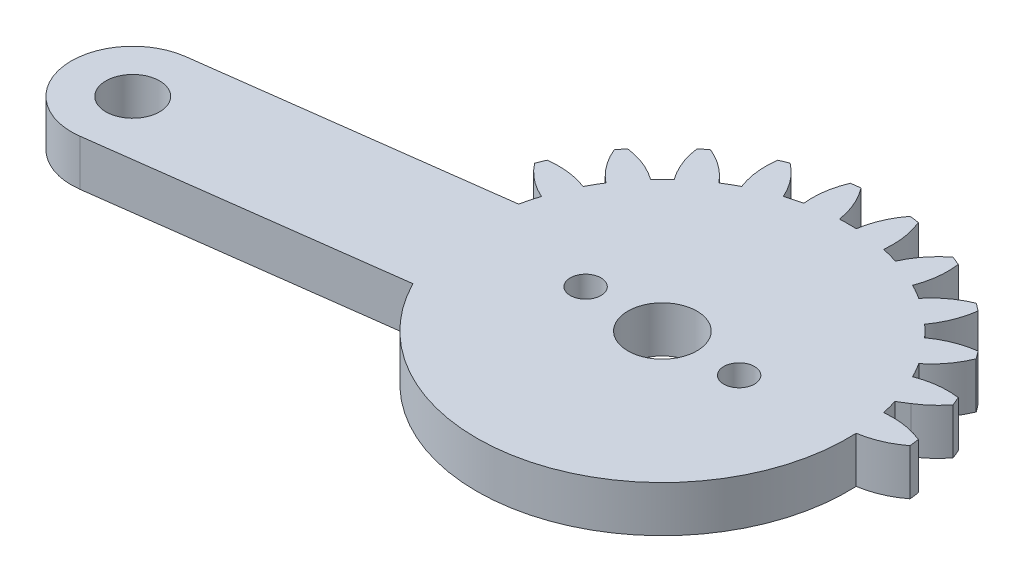
SolidWorks part; units mm, degrees
ref_plane "Front Plane" through (0, 0, 0) normal (0, 0, 1) x (1, 0, 0)
ref_plane "Top Plane" through (0, 0, 0) normal (0, 1, 0) x (1, 0, 0)
ref_plane "Right Plane" through (0, 0, 0) normal (1, 0, 0) x (0, 0, -1)
sketch "Sketch1" plane through (0, 0, 0) normal (0, 1, 0) x (1, 0, 0)
  line L0 (20.6437, 4) -> (2.0816, 4)
  line L1 (2.0816, -4) -> (20.6437, -4)
  arc A0 (2.0816, 4) -> (3.5217, 5.3071) centre (-0.7683, 8.5867) ccw
  arc A1 (3.5217, 5.3071) -> (3.2829, 5.8838) centre (-10.1063, 0) ccw
  arc A2 (3.2829, 5.8838) -> (0.6271, 5.5703) centre (2.5684, 0.5313) ccw
  arc A3 (0.6271, 5.5703) -> (0.0844, 6.5103) centre (-10.1063, 0) ccw
  arc A4 (0.0844, 6.5103) -> (1.6838, 8.6535) centre (-3.3089, 10.711) ccw
  arc A5 (1.6838, 8.6535) -> (1.3038, 9.1487) centre (-10.1063, 0) ccw
  arc A6 (1.3038, 9.1487) -> (-1.1803, 8.1585) centre (1.999, 3.7936) ccw
  arc A7 (-1.1803, 8.1585) -> (-1.9479, 8.926) centre (-10.1063, 0) ccw
  arc A8 (-1.9479, 8.926) -> (-0.9576, 11.4102) centre (-6.3127, 12.1053) ccw
  arc A9 (-0.9576, 11.4102) -> (-1.4528, 11.7901) centre (-10.1063, 0) ccw
  arc A10 (-1.4528, 11.7901) -> (-3.596, 10.1907) centre (0.6046, 6.7975) ccw
  arc A11 (-3.596, 10.1907) -> (-4.5361, 10.7334) centre (-10.1063, 0) ccw
  arc A12 (-4.5361, 10.7334) -> (-4.2225, 13.3892) centre (-9.5751, 12.6747) ccw
  arc A13 (-4.2225, 13.3892) -> (-4.7992, 13.6281) centre (-10.1063, 0) ccw
  arc A14 (-4.7992, 13.6281) -> (-6.4554, 11.5285) centre (-1.5196, 9.3381) ccw
  arc A15 (-6.4554, 11.5285) -> (-7.5039, 11.8094) centre (-10.1063, 0) ccw
  arc A16 (-7.5039, 11.8094) -> (-7.8884, 14.4558) centre (-12.8736, 12.3803) ccw
  arc A17 (-7.8884, 14.4558) -> (-8.5072, 14.5373) centre (-10.1063, 0) ccw
  arc A18 (-8.5072, 14.5373) -> (-9.5636, 12.0806) centre (-4.2291, 11.2423) ccw
  arc A19 (-9.5636, 12.0806) -> (-10.6491, 12.0806) centre (-10.1063, 0) ccw
  arc A20 (-10.6491, 12.0806) -> (-11.7054, 14.5373) centre (-15.9836, 11.2423) ccw
  arc A21 (-11.7054, 14.5373) -> (-12.3243, 14.4558) centre (-10.1063, 0) ccw
  arc A22 (-12.3243, 14.4558) -> (-12.7088, 11.8094) centre (-7.3391, 12.3803) ccw
  arc A23 (-12.7088, 11.8094) -> (-13.7573, 11.5285) centre (-10.1063, 0) ccw
  arc A24 (-13.7573, 11.5285) -> (-15.4135, 13.6281) centre (-18.6931, 9.3381) ccw
  arc A25 (-15.4135, 13.6281) -> (-15.9901, 13.3892) centre (-10.1063, 0) ccw
  arc A26 (-15.9901, 13.3892) -> (-15.6766, 10.7334) centre (-10.6376, 12.6747) ccw
  arc A27 (-15.6766, 10.7334) -> (-16.6166, 10.1907) centre (-10.1063, 0) ccw
  arc A28 (-16.6166, 10.1907) -> (-18.7599, 11.7901) centre (-20.8173, 6.7975) ccw
  arc A29 (-18.7599, 11.7901) -> (-19.255, 11.4102) centre (-10.1063, 0) ccw
  arc A30 (-19.255, 11.4102) -> (-18.2648, 8.926) centre (-13.9, 12.1053) ccw
  arc A31 (-18.2648, 8.926) -> (-19.0324, 8.1585) centre (-10.1063, 0) ccw
  arc A32 (-19.0324, 8.1585) -> (-21.5165, 9.1487) centre (-22.2117, 3.7936) ccw
  arc A33 (-21.5165, 9.1487) -> (-21.8965, 8.6535) centre (-10.1063, 0) ccw
  arc A34 (-21.8965, 8.6535) -> (-20.2971, 6.5103) centre (-16.9038, 10.711) ccw
  arc A35 (-20.2971, 6.5103) -> (-20.8398, 5.5703) centre (-10.1063, 0) ccw
  arc A36 (-20.8398, 5.5703) -> (-23.4956, 5.8838) centre (-22.7811, 0.5313) ccw
  arc A37 (-23.4956, 5.8838) -> (-23.7344, 5.3071) centre (-10.1063, 0) ccw
  arc A38 (-23.7344, 5.3071) -> (-21.6348, 3.6509) centre (-19.4444, 8.5867) ccw
  arc A39 (-21.6348, 3.6509) -> (-21.9157, 2.6025) centre (-10.1063, 0) ccw
  arc A40 (-21.9157, 2.6025) -> (-24.5622, 2.2179) centre (-22.4867, -2.7673) ccw
  arc A41 (-24.5622, 2.2179) -> (-24.6437, 1.5991) centre (-10.1063, 0) ccw
  arc A42 (-24.6437, 1.5991) -> (-22.1869, 0.5427) centre (-21.3486, 5.8773) ccw
  arc A43 (-22.1869, 0.5427) -> (-22.1869, -0.5427) centre (-10.1063, 0) ccw
  arc A44 (-22.1869, -0.5427) -> (-24.6437, -1.5991) centre (-21.3486, -5.8773) ccw
  arc A45 (-24.6437, -1.5991) -> (-24.5622, -2.2179) centre (-10.1063, 0) ccw
  arc A46 (-24.5622, -2.2179) -> (-21.9157, -2.6025) centre (-22.4867, 2.7673) ccw
  arc A47 (-21.9157, -2.6025) -> (-21.6348, -3.6509) centre (-10.1063, 0) ccw
  arc A48 (-21.6348, -3.6509) -> (-23.7344, -5.3071) centre (-19.4444, -8.5867) ccw
  arc A49 (-23.7344, -5.3071) -> (-23.4956, -5.8838) centre (-10.1063, 0) ccw
  arc A50 (-23.4956, -5.8838) -> (-20.8398, -5.5703) centre (-22.7811, -0.5313) ccw
  arc A51 (-20.8398, -5.5703) -> (-20.2971, -6.5103) centre (-10.1063, 0) ccw
  arc A52 (-20.2971, -6.5103) -> (-21.8965, -8.6535) centre (-16.9038, -10.711) ccw
  arc A53 (-21.8965, -8.6535) -> (-21.5165, -9.1487) centre (-10.1063, 0) ccw
  arc A54 (-21.5165, -9.1487) -> (-19.0324, -8.1585) centre (-22.2117, -3.7936) ccw
  arc A55 (-19.0324, -8.1585) -> (-18.2648, -8.926) centre (-10.1063, 0) ccw
  arc A56 (-18.2648, -8.926) -> (-19.255, -11.4102) centre (-13.9, -12.1053) ccw
  arc A57 (-19.255, -11.4102) -> (-18.7599, -11.7901) centre (-10.1063, 0) ccw
  arc A58 (-18.7599, -11.7901) -> (-16.6166, -10.1907) centre (-20.8173, -6.7975) ccw
  arc A59 (-16.6166, -10.1907) -> (-15.6766, -10.7334) centre (-10.1063, 0) ccw
  arc A60 (-15.6766, -10.7334) -> (-15.9901, -13.3892) centre (-10.6376, -12.6747) ccw
  arc A61 (-15.9901, -13.3892) -> (-15.4135, -13.6281) centre (-10.1063, 0) ccw
  arc A62 (-15.4135, -13.6281) -> (-13.7573, -11.5285) centre (-18.6931, -9.3381) ccw
  arc A63 (-13.7573, -11.5285) -> (-12.7088, -11.8094) centre (-10.1063, 0) ccw
  arc A64 (-12.7088, -11.8094) -> (-12.3243, -14.4558) centre (-7.3391, -12.3803) ccw
  arc A65 (-12.3243, -14.4558) -> (-11.7054, -14.5373) centre (-10.1063, 0) ccw
  arc A66 (-11.7054, -14.5373) -> (-10.6491, -12.0806) centre (-15.9836, -11.2423) ccw
  arc A67 (-10.6491, -12.0806) -> (-9.5636, -12.0806) centre (-10.1063, 0) ccw
  arc A68 (-9.5636, -12.0806) -> (-8.5072, -14.5373) centre (-4.2291, -11.2423) ccw
  arc A69 (-8.5072, -14.5373) -> (-7.8884, -14.4558) centre (-10.1063, 0) ccw
  arc A70 (-7.8884, -14.4558) -> (-7.5039, -11.8094) centre (-12.8736, -12.3803) ccw
  arc A71 (-7.5039, -11.8094) -> (-6.4554, -11.5285) centre (-10.1063, 0) ccw
  arc A72 (-6.4554, -11.5285) -> (-4.7992, -13.6281) centre (-1.5196, -9.3381) ccw
  arc A73 (-4.7992, -13.6281) -> (-4.2225, -13.3892) centre (-10.1063, 0) ccw
  arc A74 (-4.2225, -13.3892) -> (-4.5361, -10.7334) centre (-9.5751, -12.6747) ccw
  arc A75 (-4.5361, -10.7334) -> (-3.596, -10.1907) centre (-10.1063, 0) ccw
  arc A76 (-3.596, -10.1907) -> (-1.4528, -11.7901) centre (0.6046, -6.7975) ccw
  arc A77 (-1.4528, -11.7901) -> (-0.9576, -11.4102) centre (-10.1063, 0) ccw
  arc A78 (-0.9576, -11.4102) -> (-1.9479, -8.926) centre (-6.3127, -12.1053) ccw
  arc A79 (-1.9479, -8.926) -> (-1.1803, -8.1585) centre (-10.1063, 0) ccw
  arc A80 (-1.1803, -8.1585) -> (1.3038, -9.1487) centre (1.999, -3.7936) ccw
  arc A81 (1.3038, -9.1487) -> (1.6838, -8.6535) centre (-10.1063, 0) ccw
  arc A82 (1.6838, -8.6535) -> (0.0844, -6.5103) centre (-3.3089, -10.711) ccw
  arc A83 (0.0844, -6.5103) -> (0.6271, -5.5703) centre (-10.1063, 0) ccw
  arc A84 (0.6271, -5.5703) -> (3.2829, -5.8838) centre (2.5684, -0.5313) ccw
  arc A85 (3.2829, -5.8838) -> (3.5217, -5.3071) centre (-10.1063, 0) ccw
  arc A86 (3.5217, -5.3071) -> (2.0816, -4) centre (-0.7683, -8.5867) ccw
  arc A87 (20.6437, -4) -> (20.6437, 4) centre (20.6437, 0) ccw
  circle A88 centre (-10.1063, 0) radius 1.5
  circle A89 centre (20.6437, 0) radius 1.5
  dimension "D1" = 3
  dimension "D2" = 3
extrude "Boss-Extrude1" add sketch "Sketch1" along normal blind 3
sketch "Sketch3" plane through (0, 3, 0) normal (0, 1, 0) x (1, 0, 0)
  line L0 (-10.1063, 0) -> (-40.8563, 0) construction
  line L1 (-10.1063, 0) -> (-40.5933, -4.0137)
  line L2 (-10.6284, 3.9658) -> (-41.1154, -0.0479)
  line L3 (-9.5842, -3.9658) -> (-40.0712, -7.9795)
  line L4 (-10.1063, 0) -> (-4.5096, 13.5117) construction
  line L5 (-10.1063, 0) -> (-8.1974, 14.4999) construction
  circle A0 centre (-10.1063, 0) radius 1.5
  circle A1 centre (20.6437, 0) radius 1.5 construction
  circle A2 centre (20.6437, 0) radius 1.5
  circle A3 centre (-40.5933, -4.0137) radius 1.75
  circle A4 centre (-40.5933, -4.0137) radius 4
  circle A5 centre (-10.1063, 0) radius 4
  arc A6 (-4.2225, 13.3892) -> (-4.7992, 13.6281) centre (-10.1063, 0) ccw construction
  arc A7 (-7.8884, 14.4558) -> (-8.5072, 14.5373) centre (-10.1063, 0) ccw construction
  dimension "D2" = 3
  dimension "D5" = 3.5
  dimension "D6" = 8
  dimension "D7" = 8
  dimension "D1" = 30.75
  dimension "D4" = 7.5
extrude "Boss-Extrude2" add sketch "Sketch3" against normal blind 3
sketch "Sketch4" plane through (0, 3, 0) normal (0, 1, 0) x (1, 0, 0)
  line L0 (20.6437, 4) -> (2.0816, 4) construction
  line L1 (2.0816, -4) -> (20.6437, -4) construction
  line L2 (20.6437, 4) -> (2.0816, 4)
  line L3 (2.0816, -4) -> (20.6437, -4)
  line L4 (2.0816, 4) -> (1.4381, 3.6001)
  line L5 (-21.6245, -5.5509) -> (-20.8986, -5.4553)
  line L6 (-10.1063, 0) -> (0.0844, 6.5103) construction
  line L7 (-10.1063, 0) -> (1.9742, 0.5427) construction
  line L8 (-24.5755, 2.1296) -> (-41.1154, -0.0479)
  line L9 (-40.0712, -7.9795) -> (-23.5312, -5.8019)
  line L10 (2.0816, -4) -> (20.6437, -4)
  line L11 (2.0816, -4) -> (20.6437, -4)
  line L12 (-21.9429, 2.4762) -> (-41.1154, -0.0479)
  line L13 (-40.0712, -7.9795) -> (-21.6245, -5.5509)
  line L18 (20.6437, 4) -> (2.0816, 4)
  line L19 (20.6437, 4) -> (2.0816, 4)
  circle A0 centre (-10.1063, 0) radius 12.0927
  arc A1 (3.2829, 5.8838) -> (0.6271, 5.5703) centre (2.5684, 0.5313) ccw construction
  arc A2 (3.5217, 5.3071) -> (3.2829, 5.8838) centre (-10.1063, 0) ccw construction
  arc A3 (2.0816, 4) -> (3.5217, 5.3071) centre (-0.7683, 8.5867) ccw construction
  arc A4 (20.6437, -4) -> (20.6437, 4) centre (20.6437, 0) ccw construction
  arc A5 (3.5217, -5.3071) -> (2.0816, -4) centre (-0.7683, -8.5867) ccw construction
  arc A6 (3.2829, -5.8838) -> (3.5217, -5.3071) centre (-10.1063, 0) ccw construction
  arc A7 (0.6271, -5.5703) -> (3.2829, -5.8838) centre (2.5684, -0.5313) ccw construction
  arc A8 (3.2829, 5.8838) -> (0.6271, 5.5703) centre (2.5684, 0.5313) ccw
  arc A9 (3.5217, 5.3071) -> (3.2829, 5.8838) centre (-10.1063, 0) ccw
  arc A10 (2.0816, 4) -> (3.5217, 5.3071) centre (-0.7683, 8.5867) ccw
  arc A11 (20.6437, -4) -> (20.6437, 4) centre (20.6437, 0) ccw
  arc A12 (3.5217, -5.3071) -> (2.0816, -4) centre (-0.7683, -8.5867) ccw
  arc A13 (3.2829, -5.8838) -> (3.5217, -5.3071) centre (-10.1063, 0) ccw
  arc A14 (0.6271, -5.5703) -> (3.2829, -5.8838) centre (2.5684, -0.5313) ccw
  arc A15 (1.9742, 0.5427) -> (4.431, 1.5991) centre (1.1359, 5.8773) ccw
  arc A16 (4.3495, 2.2179) -> (1.7031, 2.6025) centre (2.274, -2.7673) ccw
  arc A17 (4.431, 1.5991) -> (4.3495, 2.2179) centre (-10.1063, 0) ccw
  arc A64 (-20.2971, -6.5103) -> (-21.8965, -8.6535) centre (-16.9038, -10.711) ccw
  arc A65 (-20.2971, -6.5103) -> (-21.8965, -8.6535) centre (-16.9038, -10.711) ccw
  arc A66 (-21.8965, -8.6535) -> (-21.5165, -9.1487) centre (-10.1063, 0) ccw
  arc A67 (-21.8965, -8.6535) -> (-21.5165, -9.1487) centre (-10.1063, 0) ccw
  arc A68 (-21.5165, -9.1487) -> (-19.0324, -8.1585) centre (-22.2117, -3.7936) ccw
  arc A69 (-21.5165, -9.1487) -> (-19.0324, -8.1585) centre (-22.2117, -3.7936) ccw
  arc A70 (-18.2648, -8.926) -> (-19.255, -11.4102) centre (-13.9, -12.1053) ccw
  arc A71 (-18.2648, -8.926) -> (-19.255, -11.4102) centre (-13.9, -12.1053) ccw
  arc A95 (-21.6348, 3.6509) -> (-21.9157, 2.6025) centre (-10.1063, 0) ccw
  arc A96 (-41.1154, -0.0479) -> (-40.0712, -7.9795) centre (-40.5933, -4.0137) ccw
  arc A100 (-19.0324, -8.1585) -> (-18.2648, -8.926) centre (-10.1063, 0) ccw
  arc A111 (-19.255, -11.4102) -> (-18.7599, -11.7901) centre (-10.1063, 0) ccw
  arc A112 (-19.255, -11.4102) -> (-18.7599, -11.7901) centre (-10.1063, 0) ccw
  arc A113 (-18.7599, -11.7901) -> (-16.6166, -10.1907) centre (-20.8173, -6.7975) ccw
  arc A114 (-18.7599, -11.7901) -> (-16.6166, -10.1907) centre (-20.8173, -6.7975) ccw
  arc A115 (-16.6166, -10.1907) -> (-15.6766, -10.7334) centre (-10.1063, 0) ccw
  arc A116 (-16.6166, -10.1907) -> (-15.6766, -10.7334) centre (-10.1063, 0) ccw
  arc A117 (-15.6766, -10.7334) -> (-15.9901, -13.3892) centre (-10.6376, -12.6747) ccw
  arc A118 (-15.6766, -10.7334) -> (-15.9901, -13.3892) centre (-10.6376, -12.6747) ccw
  arc A119 (-15.9901, -13.3892) -> (-15.4135, -13.6281) centre (-10.1063, 0) ccw
  arc A120 (-15.9901, -13.3892) -> (-15.4135, -13.6281) centre (-10.1063, 0) ccw
  arc A121 (-15.4135, -13.6281) -> (-13.7573, -11.5285) centre (-18.6931, -9.3381) ccw
  arc A122 (-15.4135, -13.6281) -> (-13.7573, -11.5285) centre (-18.6931, -9.3381) ccw
  arc A123 (-13.7573, -11.5285) -> (-12.7088, -11.8094) centre (-10.1063, 0) ccw
  arc A124 (-13.7573, -11.5285) -> (-12.7088, -11.8094) centre (-10.1063, 0) ccw
  arc A125 (-12.7088, -11.8094) -> (-12.3243, -14.4558) centre (-7.3391, -12.3803) ccw
  arc A126 (-12.7088, -11.8094) -> (-12.3243, -14.4558) centre (-7.3391, -12.3803) ccw
  arc A127 (-12.3243, -14.4558) -> (-11.7054, -14.5373) centre (-10.1063, 0) ccw
  arc A128 (-12.3243, -14.4558) -> (-11.7054, -14.5373) centre (-10.1063, 0) ccw
  arc A129 (-11.7054, -14.5373) -> (-10.6491, -12.0806) centre (-15.9836, -11.2423) ccw
  arc A130 (-11.7054, -14.5373) -> (-10.6491, -12.0806) centre (-15.9836, -11.2423) ccw
  arc A131 (-10.6491, -12.0806) -> (-9.5636, -12.0806) centre (-10.1063, 0) ccw
  arc A132 (-10.6491, -12.0806) -> (-9.5636, -12.0806) centre (-10.1063, 0) ccw
  arc A133 (2.0816, 4) -> (3.5217, 5.3071) centre (-0.7683, 8.5867) ccw
  arc A134 (3.5217, 5.3071) -> (3.2829, 5.8838) centre (-10.1063, 0) ccw
  arc A135 (3.2829, 5.8838) -> (0.6271, 5.5703) centre (2.5684, 0.5313) ccw
  arc A136 (0.6271, 5.5703) -> (0.0844, 6.5103) centre (-10.1063, 0) ccw
  arc A137 (0.0844, 6.5103) -> (1.6838, 8.6535) centre (-3.3089, 10.711) ccw
  arc A138 (1.6838, 8.6535) -> (1.3038, 9.1487) centre (-10.1063, 0) ccw
  arc A139 (1.3038, 9.1487) -> (-1.1803, 8.1585) centre (1.999, 3.7936) ccw
  arc A140 (-1.1803, 8.1585) -> (-1.9479, 8.926) centre (-10.1063, 0) ccw
  arc A141 (-1.9479, 8.926) -> (-0.9576, 11.4102) centre (-6.3127, 12.1053) ccw
  arc A142 (-0.9576, 11.4102) -> (-1.4528, 11.7901) centre (-10.1063, 0) ccw
  arc A143 (-1.4528, 11.7901) -> (-3.596, 10.1907) centre (0.6046, 6.7975) ccw
  arc A144 (-3.596, 10.1907) -> (-4.5361, 10.7334) centre (-10.1063, 0) ccw
  arc A145 (-4.5361, 10.7334) -> (-4.2225, 13.3892) centre (-9.5751, 12.6747) ccw
  arc A146 (-4.2225, 13.3892) -> (-4.7992, 13.6281) centre (-10.1063, 0) ccw
  arc A147 (-4.7992, 13.6281) -> (-6.4554, 11.5285) centre (-1.5196, 9.3381) ccw
  arc A148 (-6.4554, 11.5285) -> (-7.5039, 11.8094) centre (-10.1063, 0) ccw
  arc A149 (-7.5039, 11.8094) -> (-7.8884, 14.4558) centre (-12.8736, 12.3803) ccw
  arc A150 (-7.8884, 14.4558) -> (-8.5072, 14.5373) centre (-10.1063, 0) ccw
  arc A151 (-8.5072, 14.5373) -> (-9.5636, 12.0806) centre (-4.2291, 11.2423) ccw
  arc A152 (-9.5636, 12.0806) -> (-10.6491, 12.0806) centre (-10.1063, 0) ccw
  arc A153 (-10.6491, 12.0806) -> (-11.7054, 14.5373) centre (-15.9836, 11.2423) ccw
  arc A154 (-11.7054, 14.5373) -> (-12.3243, 14.4558) centre (-10.1063, 0) ccw
  arc A155 (-12.3243, 14.4558) -> (-12.7088, 11.8094) centre (-7.3391, 12.3803) ccw
  arc A156 (-12.7088, 11.8094) -> (-13.7573, 11.5285) centre (-10.1063, 0) ccw
  arc A157 (-13.7573, 11.5285) -> (-15.4135, 13.6281) centre (-18.6931, 9.3381) ccw
  arc A158 (-15.4135, 13.6281) -> (-15.9901, 13.3892) centre (-10.1063, 0) ccw
  arc A159 (-15.9901, 13.3892) -> (-15.6766, 10.7334) centre (-10.6376, 12.6747) ccw
  arc A160 (-15.6766, 10.7334) -> (-16.6166, 10.1907) centre (-10.1063, 0) ccw
  arc A161 (-16.6166, 10.1907) -> (-18.7599, 11.7901) centre (-20.8173, 6.7975) ccw
  arc A162 (-18.7599, 11.7901) -> (-19.255, 11.4102) centre (-10.1063, 0) ccw
  arc A163 (-19.255, 11.4102) -> (-18.2648, 8.926) centre (-13.9, 12.1053) ccw
  arc A164 (-18.2648, 8.926) -> (-19.0324, 8.1585) centre (-10.1063, 0) ccw
  arc A165 (-19.0324, 8.1585) -> (-21.5165, 9.1487) centre (-22.2117, 3.7936) ccw
  arc A166 (-21.5165, 9.1487) -> (-21.8965, 8.6535) centre (-10.1063, 0) ccw
  arc A167 (-21.8965, 8.6535) -> (-20.2971, 6.5103) centre (-16.9038, 10.711) ccw
  arc A168 (-20.2971, 6.5103) -> (-20.8398, 5.5703) centre (-10.1063, 0) ccw
  arc A169 (-20.8398, 5.5703) -> (-23.4956, 5.8838) centre (-22.7811, 0.5313) ccw
  arc A170 (-23.4956, 5.8838) -> (-23.7344, 5.3071) centre (-10.1063, 0) ccw
  arc A171 (-23.7344, 5.3071) -> (-21.6348, 3.6509) centre (-19.4444, 8.5867) ccw
  arc A172 (-21.6348, 3.6509) -> (-21.9157, 2.6025) centre (-10.1063, 0) ccw
  arc A173 (-9.5636, -12.0806) -> (-8.5072, -14.5373) centre (-4.2291, -11.2423) ccw
  arc A174 (-9.5636, -12.0806) -> (-8.5072, -14.5373) centre (-4.2291, -11.2423) ccw
  arc A175 (-8.5072, -14.5373) -> (-7.8884, -14.4558) centre (-10.1063, 0) ccw
  arc A176 (-41.1154, -0.0479) -> (-40.0712, -7.9795) centre (-40.5933, -4.0137) ccw
  arc A177 (-8.5072, -14.5373) -> (-7.8884, -14.4558) centre (-10.1063, 0) ccw
  arc A178 (-7.8884, -14.4558) -> (-7.5039, -11.8094) centre (-12.8736, -12.3803) ccw
  arc A179 (-7.8884, -14.4558) -> (-7.5039, -11.8094) centre (-12.8736, -12.3803) ccw
  arc A180 (-19.0324, -8.1585) -> (-18.2648, -8.926) centre (-10.1063, 0) ccw
  arc A181 (-7.5039, -11.8094) -> (-6.4554, -11.5285) centre (-10.1063, 0) ccw
  arc A182 (-7.5039, -11.8094) -> (-6.4554, -11.5285) centre (-10.1063, 0) ccw
  arc A183 (-6.4554, -11.5285) -> (-4.7992, -13.6281) centre (-1.5196, -9.3381) ccw
  arc A184 (-6.4554, -11.5285) -> (-4.7992, -13.6281) centre (-1.5196, -9.3381) ccw
  arc A185 (-4.7992, -13.6281) -> (-4.2225, -13.3892) centre (-10.1063, 0) ccw
  arc A186 (-4.7992, -13.6281) -> (-4.2225, -13.3892) centre (-10.1063, 0) ccw
  arc A187 (-4.2225, -13.3892) -> (-4.5361, -10.7334) centre (-9.5751, -12.6747) ccw
  arc A188 (-4.2225, -13.3892) -> (-4.5361, -10.7334) centre (-9.5751, -12.6747) ccw
  arc A189 (-4.5361, -10.7334) -> (-3.596, -10.1907) centre (-10.1063, 0) ccw
  arc A190 (-4.5361, -10.7334) -> (-3.596, -10.1907) centre (-10.1063, 0) ccw
  arc A191 (-3.596, -10.1907) -> (-1.4528, -11.7901) centre (0.6046, -6.7975) ccw
  arc A192 (-3.596, -10.1907) -> (-1.4528, -11.7901) centre (0.6046, -6.7975) ccw
  arc A193 (-1.4528, -11.7901) -> (-0.9576, -11.4102) centre (-10.1063, 0) ccw
  arc A194 (-1.4528, -11.7901) -> (-0.9576, -11.4102) centre (-10.1063, 0) ccw
  arc A195 (-0.9576, -11.4102) -> (-1.9479, -8.926) centre (-6.3127, -12.1053) ccw
  arc A196 (-0.9576, -11.4102) -> (-1.9479, -8.926) centre (-6.3127, -12.1053) ccw
  arc A197 (-1.9479, -8.926) -> (-1.1803, -8.1585) centre (-10.1063, 0) ccw
  arc A198 (-1.9479, -8.926) -> (-1.1803, -8.1585) centre (-10.1063, 0) ccw
  arc A199 (-1.1803, -8.1585) -> (1.3038, -9.1487) centre (1.999, -3.7936) ccw
  arc A200 (-1.1803, -8.1585) -> (1.3038, -9.1487) centre (1.999, -3.7936) ccw
  arc A201 (1.3038, -9.1487) -> (1.6838, -8.6535) centre (-10.1063, 0) ccw
  arc A202 (1.3038, -9.1487) -> (1.6838, -8.6535) centre (-10.1063, 0) ccw
  arc A203 (1.6838, -8.6535) -> (0.0844, -6.5103) centre (-3.3089, -10.711) ccw
  arc A204 (1.6838, -8.6535) -> (0.0844, -6.5103) centre (-3.3089, -10.711) ccw
  arc A205 (0.0844, -6.5103) -> (0.6271, -5.5703) centre (-10.1063, 0) ccw
  arc A206 (0.0844, -6.5103) -> (0.6271, -5.5703) centre (-10.1063, 0) ccw
  arc A207 (0.6271, -5.5703) -> (3.2829, -5.8838) centre (2.5684, -0.5313) ccw
  arc A208 (0.6271, -5.5703) -> (3.2829, -5.8838) centre (2.5684, -0.5313) ccw
  arc A209 (3.2829, -5.8838) -> (3.5217, -5.3071) centre (-10.1063, 0) ccw
  arc A210 (3.2829, -5.8838) -> (3.5217, -5.3071) centre (-10.1063, 0) ccw
  arc A211 (3.5217, -5.3071) -> (2.0816, -4) centre (-0.7683, -8.5867) ccw
  arc A212 (3.5217, -5.3071) -> (2.0816, -4) centre (-0.7683, -8.5867) ccw
  arc A213 (2.0816, 4) -> (3.5217, 5.3071) centre (-0.7683, 8.5867) ccw
  arc A214 (3.5217, 5.3071) -> (3.2829, 5.8838) centre (-10.1063, 0) ccw
  arc A215 (3.2829, 5.8838) -> (0.6271, 5.5703) centre (2.5684, 0.5313) ccw
  arc A216 (0.6271, 5.5703) -> (0.0844, 6.5103) centre (-10.1063, 0) ccw
  arc A217 (0.0844, 6.5103) -> (1.6838, 8.6535) centre (-3.3089, 10.711) ccw
  arc A218 (1.6838, 8.6535) -> (1.3038, 9.1487) centre (-10.1063, 0) ccw
  arc A219 (1.3038, 9.1487) -> (-1.1803, 8.1585) centre (1.999, 3.7936) ccw
  arc A220 (-1.1803, 8.1585) -> (-1.9479, 8.926) centre (-10.1063, 0) ccw
  arc A221 (-1.9479, 8.926) -> (-0.9576, 11.4102) centre (-6.3127, 12.1053) ccw
  arc A222 (-0.9576, 11.4102) -> (-1.4528, 11.7901) centre (-10.1063, 0) ccw
  arc A223 (-1.4528, 11.7901) -> (-3.596, 10.1907) centre (0.6046, 6.7975) ccw
  arc A224 (-3.596, 10.1907) -> (-4.5361, 10.7334) centre (-10.1063, 0) ccw
  arc A225 (-4.5361, 10.7334) -> (-4.2225, 13.3892) centre (-9.5751, 12.6747) ccw
  arc A226 (-4.2225, 13.3892) -> (-4.7992, 13.6281) centre (-10.1063, 0) ccw
  arc A227 (-4.7992, 13.6281) -> (-6.4554, 11.5285) centre (-1.5196, 9.3381) ccw
  arc A228 (-6.4554, 11.5285) -> (-7.5039, 11.8094) centre (-10.1063, 0) ccw
  arc A229 (-7.5039, 11.8094) -> (-7.8884, 14.4558) centre (-12.8736, 12.3803) ccw
  arc A230 (-7.8884, 14.4558) -> (-8.5072, 14.5373) centre (-10.1063, 0) ccw
  arc A231 (-8.5072, 14.5373) -> (-9.5636, 12.0806) centre (-4.2291, 11.2423) ccw
  arc A232 (-9.5636, 12.0806) -> (-10.6491, 12.0806) centre (-10.1063, 0) ccw
  arc A233 (-10.6491, 12.0806) -> (-11.7054, 14.5373) centre (-15.9836, 11.2423) ccw
  arc A234 (-11.7054, 14.5373) -> (-12.3243, 14.4558) centre (-10.1063, 0) ccw
  arc A235 (-12.3243, 14.4558) -> (-12.7088, 11.8094) centre (-7.3391, 12.3803) ccw
  arc A236 (-12.7088, 11.8094) -> (-13.7573, 11.5285) centre (-10.1063, 0) ccw
  arc A237 (-13.7573, 11.5285) -> (-15.4135, 13.6281) centre (-18.6931, 9.3381) ccw
  arc A238 (-15.4135, 13.6281) -> (-15.9901, 13.3892) centre (-10.1063, 0) ccw
  arc A239 (-15.9901, 13.3892) -> (-15.6766, 10.7334) centre (-10.6376, 12.6747) ccw
  arc A240 (-15.6766, 10.7334) -> (-16.6166, 10.1907) centre (-10.1063, 0) ccw
  arc A241 (-16.6166, 10.1907) -> (-18.7599, 11.7901) centre (-20.8173, 6.7975) ccw
  arc A242 (-18.7599, 11.7901) -> (-19.255, 11.4102) centre (-10.1063, 0) ccw
  arc A243 (-19.255, 11.4102) -> (-18.2648, 8.926) centre (-13.9, 12.1053) ccw
  arc A244 (-18.2648, 8.926) -> (-19.0324, 8.1585) centre (-10.1063, 0) ccw
  arc A245 (-19.0324, 8.1585) -> (-21.5165, 9.1487) centre (-22.2117, 3.7936) ccw
  arc A246 (-21.5165, 9.1487) -> (-21.8965, 8.6535) centre (-10.1063, 0) ccw
  arc A247 (-21.8965, 8.6535) -> (-20.2971, 6.5103) centre (-16.9038, 10.711) ccw
  arc A248 (-20.2971, 6.5103) -> (-20.8398, 5.5703) centre (-10.1063, 0) ccw
  arc A249 (-20.8398, 5.5703) -> (-23.4956, 5.8838) centre (-22.7811, 0.5313) ccw
  arc A250 (-23.4956, 5.8838) -> (-23.7344, 5.3071) centre (-10.1063, 0) ccw
  arc A251 (-23.7344, 5.3071) -> (-21.6348, 3.6509) centre (-19.4444, 8.5867) ccw
  arc A252 (20.6437, -4) -> (20.6437, 4) centre (20.6437, 0) ccw
  arc A253 (20.6437, -4) -> (20.6437, 4) centre (20.6437, 0) ccw
  arc A254 (-21.9157, 2.6025) -> (-24.5622, 2.2179) centre (-22.4867, -2.7673) ccw
  arc A255 (-21.9157, 2.6025) -> (-24.5622, 2.2179) centre (-22.4867, -2.7673) ccw
  arc A256 (-24.5622, 2.2179) -> (-24.5755, 2.1296) centre (-10.1063, 0) ccw
  arc A257 (-24.5622, 2.2179) -> (-24.5755, 2.1296) centre (-10.1063, 0) ccw
  arc A258 (-23.5312, -5.8019) -> (-23.4956, -5.8838) centre (-10.1063, 0) ccw
  arc A259 (-23.5312, -5.8019) -> (-23.4956, -5.8838) centre (-10.1063, 0) ccw
  arc A260 (-23.4956, -5.8838) -> (-20.8398, -5.5703) centre (-22.7811, -0.5313) ccw
  arc A261 (-23.4956, -5.8838) -> (-20.8398, -5.5703) centre (-22.7811, -0.5313) ccw
  arc A262 (-20.8398, -5.5703) -> (-20.2971, -6.5103) centre (-10.1063, 0) ccw
  arc A263 (-20.8398, -5.5703) -> (-20.2971, -6.5103) centre (-10.1063, 0) ccw
  point P40 (-10.1063, 0)
  dimension "D2" = 24.1855
  dimension "D4" = 30
  dimension "D1" = 0
  dimension "D3" = 2
extrude "Cut-Extrude1" cut sketch "Sketch4" against normal blind 4 contours A67 A69 A0 L5 A65 | A112 A114 A0 A71 | A120 A122 A0 A118 | A128 A130 A0 A126 | A177 A179 A0 A174 | A186 A188 A0 A184 | A194 A196 A0 A192 | A202 A204 A0 A200 | A255 A257 L12 A0 | L13 A259 A261 A0 L5 | A0 A14 A13 A12 L3 A11 L2 L4
sketch "Sketch5" plane through (0, 3, 0) normal (0, 1, 0) x (1, 0, 0)
  circle A0 centre (-10.1063, 0) radius 2.25
  circle A1 centre (-5.1063, 0) radius 1
  circle A2 centre (-15.1063, 0) radius 1
  circle A3 centre (-10.1063, 0) radius 1.5 construction
  dimension "D1" = 4.5
  dimension "D2" = 2
  dimension "D3" = 2
  dimension "D4" = 5
  dimension "D5" = 10
extrude "Cut-Extrude2" cut sketch "Sketch5" against normal up to next contours A2 | A1 | A0
